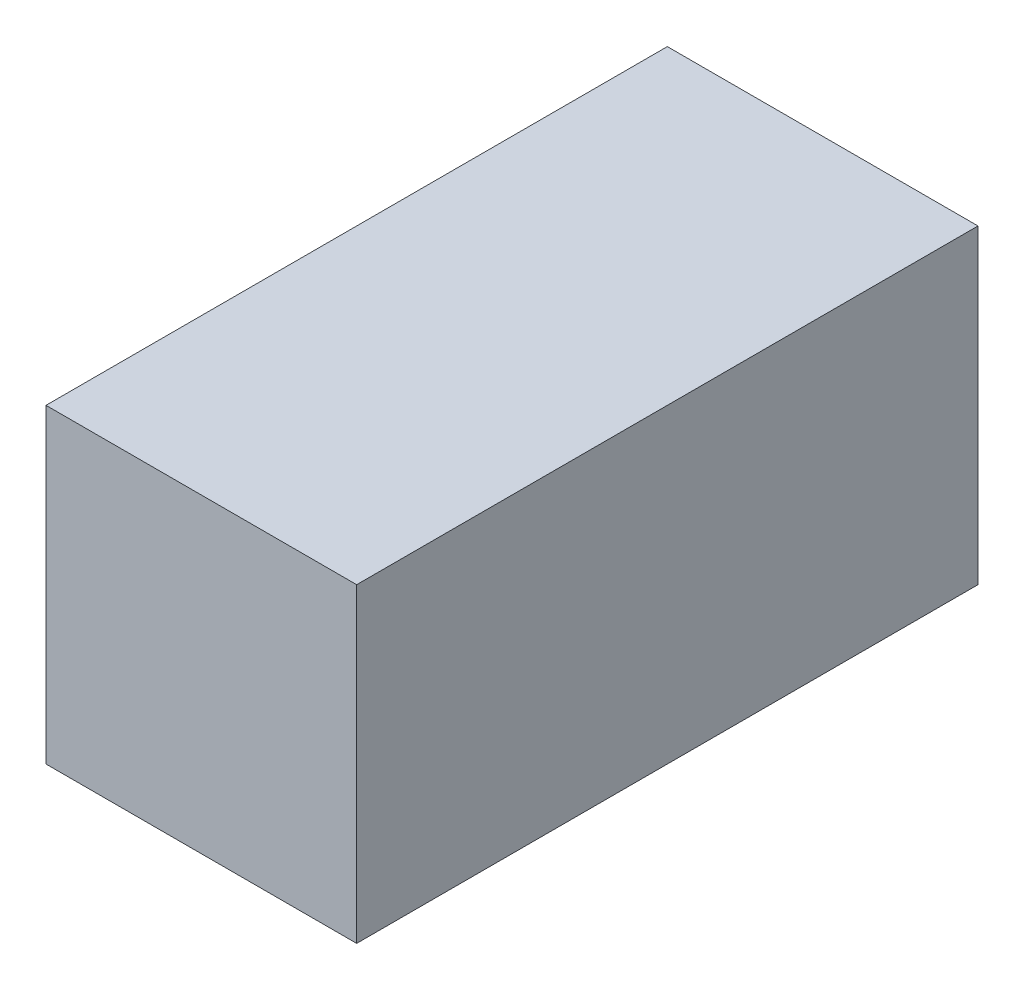
SolidWorks part; units mm, degrees
ref_plane "Piano frontale" through (0, 0, 0) normal (0, 0, 1) x (1, 0, 0)
ref_plane "Piano superiore" through (0, 0, 0) normal (0, 1, 0) x (1, 0, 0)
ref_plane "Piano destro" through (0, 0, 0) normal (1, 0, 0) x (0, 0, -1)
sketch "Schizzo1" plane through (0, 0, 0) normal (0, 0, 1) x (1, 0, 0)
  line L1 (5, -5) -> (-5, -5)
  line L2 (5, -5) -> (5, 5)
  line L3 (5, 5) -> (-5, 5)
  line L4 (-5, -5) -> (-5, 5)
  line L5 (5, -5) -> (-5, 5) construction
  line L6 (5, 5) -> (-5, -5) construction
  point P0 (0, 0)
  dimension "D1" = 10
  dimension "D2" = 10
extrude "Estrusione-Estrusione1" add sketch "Schizzo1" along normal blind 20
sketch "Schizzo2" plane through (0, 0, 0) normal (0, 1, 0) x (1, 0, 0)
  line L1 (5, -20) -> (20, -20)
  line L2 (5, -20) -> (5, -14)
  line L3 (5, -14) -> (20, -14)
  line L4 (20, -20) -> (20, -14)
  dimension "D1" = 6
  dimension "D2" = 15
extrude "Estrusione-Estrusione2" [suppressed] add sketch "Schizzo2" along normal mid plane 10
